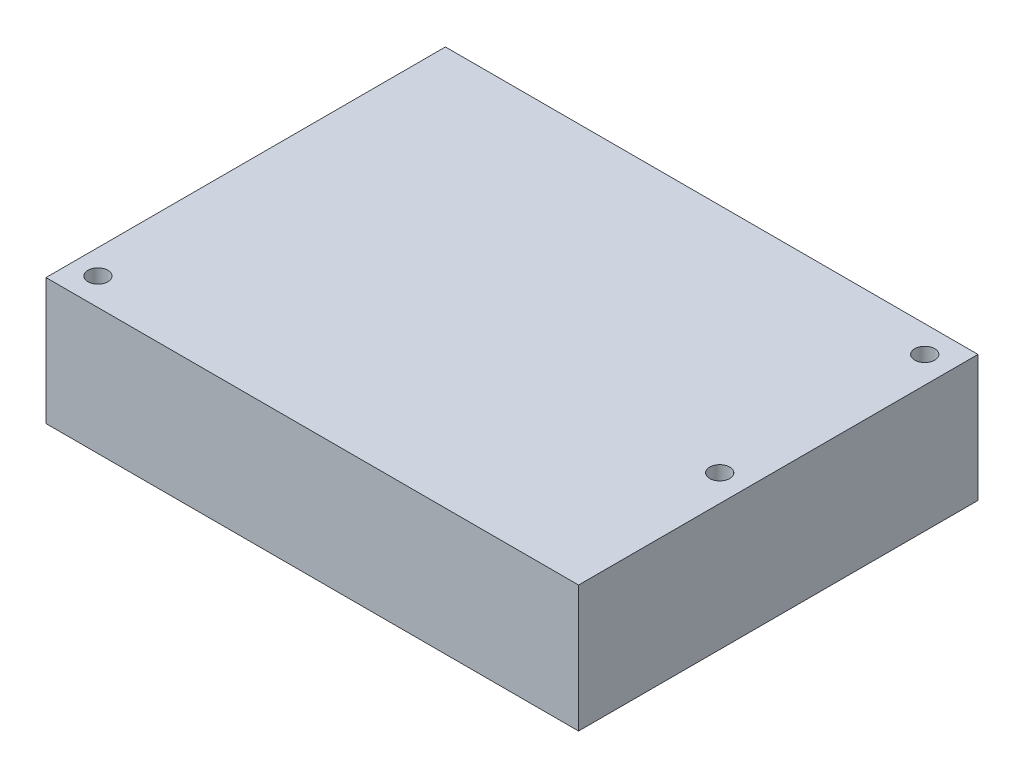
SolidWorks part; units mm, degrees
ref_plane "Front Plane" through (0, 0, 0) normal (0, 0, 1) x (1, 0, 0)
ref_plane "Top Plane" through (0, 0, 0) normal (0, 1, 0) x (1, 0, 0)
ref_plane "Right Plane" through (0, 0, 0) normal (1, 0, 0) x (0, 0, -1)
sketch "Sketch1" plane through (0, 0, 0) normal (0, 1, 0) x (1, 0, 0)
  line L1 (-40, -30) -> (40, -30)
  line L2 (-40, -30) -> (-40, 30)
  line L3 (-40, 30) -> (40, 30)
  line L4 (40, -30) -> (40, 30)
  line L5 (-40, -30) -> (40, 30) construction
  line L6 (-40, 30) -> (40, -30) construction
  circle A0 centre (36, 26) radius 1.5
  circle A1 centre (36, -4.8) radius 1.5
  circle A2 centre (-36.3, -25.9) radius 1.5
  point P0 (0, 0)
  dimension "D3" = 3
  dimension "D4" = 4
  dimension "D5" = 4
  dimension "D6" = 4
  dimension "D7" = 30.8
  dimension "D8" = 4.1
  dimension "D9" = 3.7
  dimension "D1" = 80
  dimension "D2" = 60
extrude "Boss-Extrude1" add sketch "Sketch1" along normal blind 19
